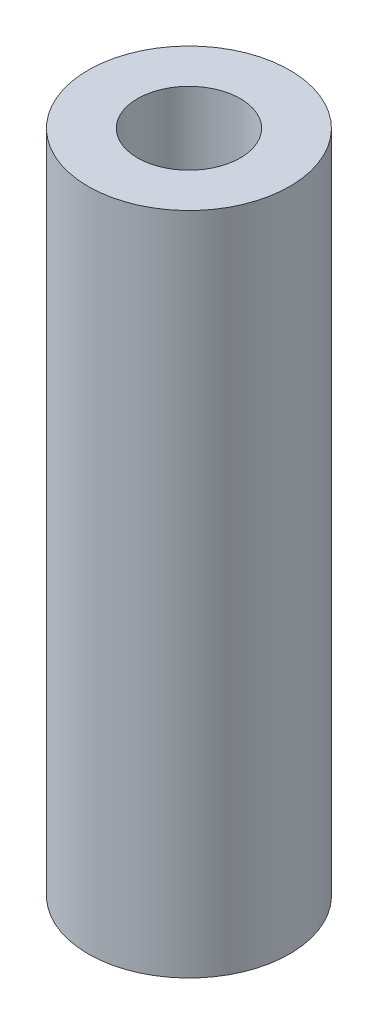
SolidWorks part; units mm, degrees
material "6061 Alloy"
ref_plane "Front Plane" through (0, 0, 0) normal (0, 0, 1) x (1, 0, 0)
ref_plane "Top Plane" through (0, 0, 0) normal (0, 1, 0) x (1, 0, 0)
ref_plane "Right Plane" through (0, 0, 0) normal (1, 0, 0) x (0, 0, -1)
sketch "Sketch1" plane through (0, 0, 0) normal (0, 1, 0) x (1, 0, 0)
  circle A0 centre (0, 0) radius 3.9688
  circle A1 centre (0, 0) radius 7.7787
  dimension "D1" = 7.9375
  dimension "D2" = 3.81
extrude "Boss-Extrude1" add sketch "Sketch1" along normal blind 51.308
